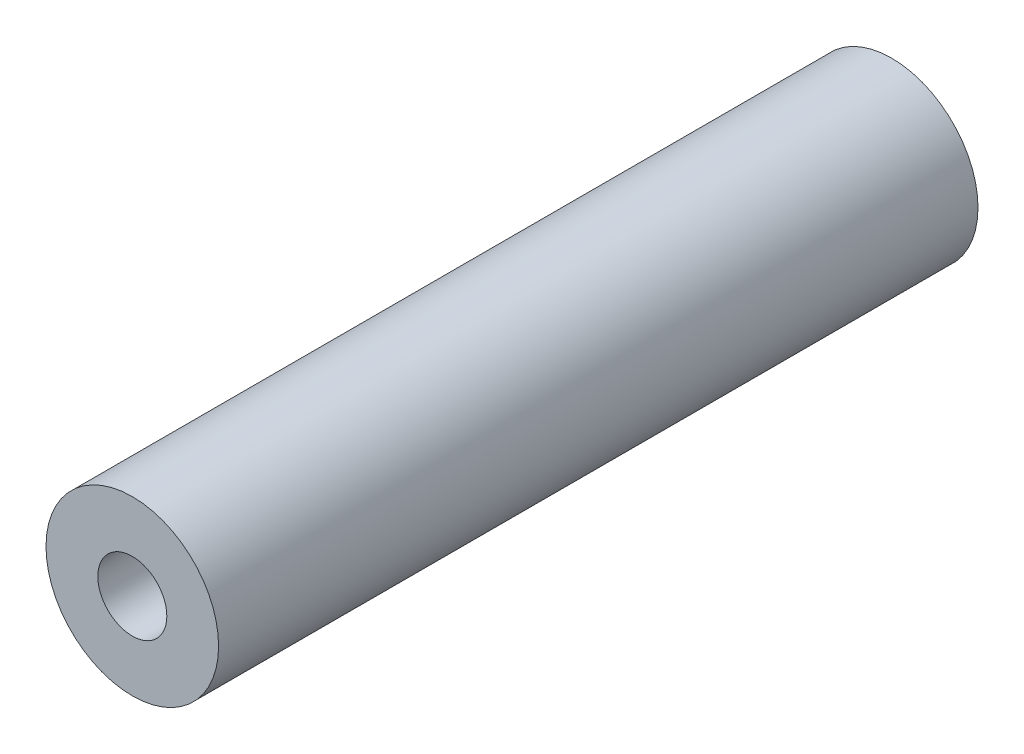
SolidWorks part; units mm, degrees
ref_plane "前视基准面" through (0, 0, 0) normal (0, 0, 1) x (1, 0, 0)
ref_plane "上视基准面" through (0, 0, 0) normal (0, 1, 0) x (1, 0, 0)
ref_plane "右视基准面" through (0, 0, 0) normal (1, 0, 0) x (0, 0, -1)
other "Configuration Table"
sketch "草图1" plane through (0, 0, 0) normal (0, 0, 1) x (1, 0, 0)
  circle A0 centre (0, 0) radius 2.5
  dimension "D1" = 5
extrude "拉伸-薄壁1" add sketch "草图1" against normal blind 22 thin thin type one direction reverse wall 1.5
